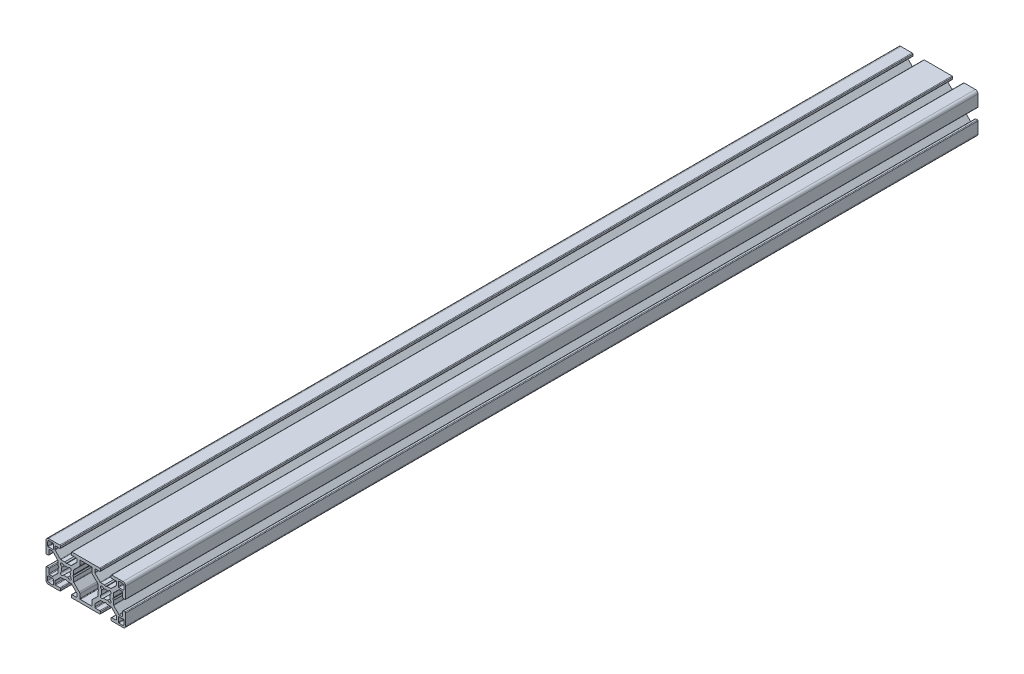
SolidWorks part; units mm, degrees
material "6105-T5 Aluminum"
ref_plane "Front Plane" through (0, 0, 0) normal (0, 0, 1) x (1, 0, 0)
ref_plane "Top Plane" through (0, 0, 0) normal (0, 1, 0) x (1, 0, 0)
ref_plane "Right Plane" through (0, 0, 0) normal (1, 0, 0) x (0, 0, -1)
sketch "Sketch1" plane through (0, 0, 0) normal (0, 0, 1) x (1, 0, 0)
  line L0 (12.7825, 3.7261) -> (13.5257, 2.983)
  line L1 (16.4743, 2.983) -> (17.2175, 3.7261)
  line L2 (18.7261, 2.2175) -> (17.983, 1.4743)
  line L3 (17.983, -1.4743) -> (18.7261, -2.2175)
  line L4 (17.2175, -3.7261) -> (16.4743, -2.983)
  line L5 (13.5257, -2.983) -> (12.7825, -3.7261)
  line L6 (11.2739, -2.2175) -> (12.017, -1.4743)
  line L7 (12.017, 1.4743) -> (11.2739, 2.2175)
  line L8 (-28.7046, 9.8946) -> (-28.7046, 12.6886)
  line L9 (-27.6886, 13.7046) -> (-24.8946, 13.7046)
  line L10 (-24.5136, 13.3236) -> (-24.5136, 9.8946)
  line L11 (-24.8946, 9.5136) -> (-28.3236, 9.5136)
  line L12 (-24.8946, -13.7046) -> (-27.6886, -13.7046)
  line L13 (-28.7046, -12.6886) -> (-28.7046, -9.8946)
  line L14 (-28.3236, -9.5136) -> (-24.8946, -9.5136)
  line L15 (-24.5136, -9.8946) -> (-24.5136, -13.3236)
  line L16 (4.9816, 8.2224) -> (9.0292, 4.1748)
  line L17 (9.178, 3.8155) -> (9.178, 0.9525)
  line L18 (9.178, 0.9525) -> (9.686, 0)
  line L19 (9.686, 0) -> (9.178, -0.9525)
  line L20 (9.178, -0.9525) -> (9.178, -3.8155)
  line L21 (9.0292, -4.1748) -> (4.9816, -8.2224)
  line L22 (4.5352, -9.3) -> (4.5352, -12.4092)
  line L23 (4.1542, -12.7902) -> (-4.1542, -12.7902)
  line L24 (-4.5352, -12.4092) -> (-4.5352, -9.3)
  line L25 (-4.9816, -8.2224) -> (-9.0292, -4.1748)
  line L26 (-9.178, -3.8155) -> (-9.178, -0.9525)
  line L27 (-9.178, -0.9525) -> (-9.686, 0)
  line L28 (-9.686, 0) -> (-9.178, 0.9525)
  line L29 (-9.178, 0.9525) -> (-9.178, 3.8155)
  line L30 (-9.0292, 4.1748) -> (-4.9816, 8.2224)
  line L31 (-4.5352, 9.3) -> (-4.5352, 12.4092)
  line L32 (-4.1542, 12.7902) -> (4.1542, 12.7902)
  line L33 (4.5352, 12.4092) -> (4.5352, 9.3)
  line L34 (-18.7261, -2.2175) -> (-17.983, -1.4743)
  line L35 (-17.983, 1.4743) -> (-18.7261, 2.2175)
  line L36 (-17.2175, 3.7261) -> (-16.4743, 2.983)
  line L37 (-13.5257, 2.983) -> (-12.7825, 3.7261)
  line L38 (-11.2739, 2.2175) -> (-12.017, 1.4743)
  line L39 (-12.017, -1.4743) -> (-11.2739, -2.2175)
  line L40 (-12.7825, -3.7261) -> (-13.5257, -2.983)
  line L41 (-16.4743, -2.983) -> (-17.2175, -3.7261)
  line L42 (24.8946, 13.7046) -> (27.6886, 13.7046)
  line L43 (28.7046, 12.6886) -> (28.7046, 9.8946)
  line L44 (28.3236, 9.5136) -> (24.8946, 9.5136)
  line L45 (24.5136, 9.8946) -> (24.5136, 13.3236)
  line L46 (24.5136, -13.3236) -> (24.5136, -9.8946)
  line L47 (24.8946, -9.5136) -> (28.3236, -9.5136)
  line L48 (28.7046, -9.8946) -> (28.7046, -12.6886)
  line L49 (27.6886, -13.7046) -> (24.8946, -13.7046)
  line L50 (-10.428, -15) -> (10.428, -15)
  line L51 (10.936, -14.492) -> (10.936, -13.2982)
  line L52 (10.428, -12.7902) -> (7.253, -12.7902)
  line L53 (6.745, -12.2822) -> (6.745, -10.2615)
  line L54 (6.8938, -9.9023) -> (10.8252, -5.9708)
  line L55 (11.1845, -5.822) -> (14.0475, -5.822)
  line L56 (14.0475, -5.822) -> (15, -5.314)
  line L57 (15, -5.314) -> (15.9525, -5.822)
  line L58 (15.9525, -5.822) -> (18.8155, -5.822)
  line L59 (19.1748, -5.9708) -> (23.1062, -9.9023)
  line L60 (23.255, -10.2615) -> (23.255, -12.2822)
  line L61 (22.747, -12.7902) -> (19.572, -12.7902)
  line L62 (19.064, -13.2982) -> (19.064, -14.492)
  line L63 (19.572, -15) -> (27.9934, -15)
  line L64 (30, -12.9934) -> (30, -4.572)
  line L65 (29.492, -4.064) -> (28.2982, -4.064)
  line L66 (27.7902, -4.572) -> (27.7902, -7.747)
  line L67 (27.2822, -8.255) -> (25.2615, -8.255)
  line L68 (24.9023, -8.1062) -> (20.9708, -4.1748)
  line L69 (20.822, -3.8155) -> (20.822, -0.9525)
  line L70 (20.822, -0.9525) -> (20.314, 0)
  line L71 (20.314, 0) -> (20.822, 0.9525)
  line L72 (20.822, 0.9525) -> (20.822, 3.8155)
  line L73 (20.9708, 4.1748) -> (24.9023, 8.1062)
  line L74 (25.2615, 8.255) -> (27.2822, 8.255)
  line L75 (27.7902, 7.747) -> (27.7902, 4.572)
  line L76 (28.2982, 4.064) -> (29.492, 4.064)
  line L77 (30, 4.572) -> (30, 12.9934)
  line L78 (27.9934, 15) -> (19.572, 15)
  line L79 (19.064, 14.492) -> (19.064, 13.2982)
  line L80 (19.572, 12.7902) -> (22.747, 12.7902)
  line L81 (23.255, 12.2822) -> (23.255, 10.2615)
  line L82 (23.1062, 9.9023) -> (19.1748, 5.9708)
  line L83 (18.8155, 5.822) -> (15.9525, 5.822)
  line L84 (15.9525, 5.822) -> (15, 5.314)
  line L85 (15, 5.314) -> (14.0475, 5.822)
  line L86 (14.0475, 5.822) -> (11.1845, 5.822)
  line L87 (10.8252, 5.9708) -> (6.8938, 9.9023)
  line L88 (6.745, 10.2615) -> (6.745, 12.2822)
  line L89 (7.253, 12.7902) -> (10.428, 12.7902)
  line L90 (10.936, 13.2982) -> (10.936, 14.492)
  line L91 (10.428, 15) -> (-10.428, 15)
  line L92 (-10.936, 14.492) -> (-10.936, 13.2982)
  line L93 (-10.428, 12.7902) -> (-7.253, 12.7902)
  line L94 (-6.745, 12.2822) -> (-6.745, 10.2615)
  line L95 (-6.8938, 9.9023) -> (-10.8252, 5.9708)
  line L96 (-11.1845, 5.822) -> (-14.0475, 5.822)
  line L97 (-14.0475, 5.822) -> (-15, 5.314)
  line L98 (-15, 5.314) -> (-15.9525, 5.822)
  line L99 (-15.9525, 5.822) -> (-18.8155, 5.822)
  line L100 (-19.1748, 5.9708) -> (-23.1062, 9.9023)
  line L101 (-23.255, 10.2615) -> (-23.255, 12.2822)
  line L102 (-22.747, 12.7902) -> (-19.572, 12.7902)
  line L103 (-19.064, 13.2982) -> (-19.064, 14.492)
  line L104 (-19.572, 15) -> (-27.9934, 15)
  line L105 (-30, 12.9934) -> (-30, 4.572)
  line L106 (-29.492, 4.064) -> (-28.2982, 4.064)
  line L107 (-27.7902, 4.572) -> (-27.7902, 7.747)
  line L108 (-27.2822, 8.255) -> (-25.2615, 8.255)
  line L109 (-24.9023, 8.1062) -> (-20.9708, 4.1748)
  line L110 (-20.822, 3.8155) -> (-20.822, 0.9525)
  line L111 (-20.822, 0.9525) -> (-20.314, 0)
  line L112 (-20.314, 0) -> (-20.822, -0.9525)
  line L113 (-20.822, -0.9525) -> (-20.822, -3.8155)
  line L114 (-20.9708, -4.1748) -> (-24.9023, -8.1062)
  line L115 (-25.2615, -8.255) -> (-27.2822, -8.255)
  line L116 (-27.7902, -7.747) -> (-27.7902, -4.572)
  line L117 (-28.2982, -4.064) -> (-29.492, -4.064)
  line L118 (-30, -4.572) -> (-30, -12.9934)
  line L119 (-27.9934, -15) -> (-19.572, -15)
  line L120 (-19.064, -14.492) -> (-19.064, -13.2982)
  line L121 (-19.572, -12.7902) -> (-22.747, -12.7902)
  line L122 (-23.255, -12.2822) -> (-23.255, -10.2615)
  line L123 (-23.1062, -9.9023) -> (-19.1748, -5.9708)
  line L124 (-18.8155, -5.822) -> (-15.9525, -5.822)
  line L125 (-15.9525, -5.822) -> (-15, -5.314)
  line L126 (-15, -5.314) -> (-14.0475, -5.822)
  line L127 (-14.0475, -5.822) -> (-11.1845, -5.822)
  line L128 (-10.8252, -5.9708) -> (-6.8938, -9.9023)
  line L129 (-6.745, -10.2615) -> (-6.745, -12.2822)
  line L130 (-7.253, -12.7902) -> (-10.428, -12.7902)
  line L131 (-10.936, -13.2982) -> (-10.936, -14.492)
  arc A0 (12.7825, 3.7261) -> (11.2739, 2.2175) centre (12.0282, 2.9718) ccw
  arc A1 (16.4743, 2.983) -> (13.5257, 2.983) centre (15, 0) ccw
  arc A2 (18.7261, 2.2175) -> (17.2175, 3.7261) centre (17.9718, 2.9718) ccw
  arc A3 (17.983, -1.4743) -> (17.983, 1.4743) centre (15, 0) ccw
  arc A4 (17.2175, -3.7261) -> (18.7261, -2.2175) centre (17.9718, -2.9718) ccw
  arc A5 (13.5257, -2.983) -> (16.4743, -2.983) centre (15, 0) ccw
  arc A6 (11.2739, -2.2175) -> (12.7825, -3.7261) centre (12.0282, -2.9718) ccw
  arc A7 (12.017, 1.4743) -> (12.017, -1.4743) centre (15, 0) ccw
  arc A8 (-28.7046, 9.8946) -> (-28.3236, 9.5136) centre (-28.3236, 9.8946) ccw
  arc A9 (-27.6886, 13.7046) -> (-28.7046, 12.6886) centre (-27.6886, 12.6886) ccw
  arc A10 (-24.5136, 13.3236) -> (-24.8946, 13.7046) centre (-24.8946, 13.3236) ccw
  arc A11 (-24.8946, 9.5136) -> (-24.5136, 9.8946) centre (-24.8946, 9.8946) ccw
  arc A12 (-24.8946, -13.7046) -> (-24.5136, -13.3236) centre (-24.8946, -13.3236) ccw
  arc A13 (-28.7046, -12.6886) -> (-27.6886, -13.7046) centre (-27.6886, -12.6886) ccw
  arc A14 (-28.3236, -9.5136) -> (-28.7046, -9.8946) centre (-28.3236, -9.8946) ccw
  arc A15 (-24.5136, -9.8946) -> (-24.8946, -9.5136) centre (-24.8946, -9.8946) ccw
  arc A16 (4.5352, 9.3) -> (4.9816, 8.2224) centre (6.0592, 9.3) ccw
  arc A17 (9.178, 3.8155) -> (9.0292, 4.1748) centre (8.67, 3.8155) ccw
  arc A18 (9.0292, -4.1748) -> (9.178, -3.8155) centre (8.67, -3.8155) ccw
  arc A19 (4.9816, -8.2224) -> (4.5352, -9.3) centre (6.0592, -9.3) ccw
  arc A20 (4.1542, -12.7902) -> (4.5352, -12.4092) centre (4.1542, -12.4092) ccw
  arc A21 (-4.5352, -12.4092) -> (-4.1542, -12.7902) centre (-4.1542, -12.4092) ccw
  arc A22 (-4.5352, -9.3) -> (-4.9816, -8.2224) centre (-6.0592, -9.3) ccw
  arc A23 (-9.178, -3.8155) -> (-9.0292, -4.1748) centre (-8.67, -3.8155) ccw
  arc A24 (-9.0292, 4.1748) -> (-9.178, 3.8155) centre (-8.67, 3.8155) ccw
  arc A25 (-4.9816, 8.2224) -> (-4.5352, 9.3) centre (-6.0592, 9.3) ccw
  arc A26 (-4.1542, 12.7902) -> (-4.5352, 12.4092) centre (-4.1542, 12.4092) ccw
  arc A27 (4.5352, 12.4092) -> (4.1542, 12.7902) centre (4.1542, 12.4092) ccw
  arc A28 (-18.7261, -2.2175) -> (-17.2175, -3.7261) centre (-17.9718, -2.9718) ccw
  arc A29 (-17.983, 1.4743) -> (-17.983, -1.4743) centre (-15, 0) ccw
  arc A30 (-17.2175, 3.7261) -> (-18.7261, 2.2175) centre (-17.9718, 2.9718) ccw
  arc A31 (-13.5257, 2.983) -> (-16.4743, 2.983) centre (-15, 0) ccw
  arc A32 (-11.2739, 2.2175) -> (-12.7825, 3.7261) centre (-12.0282, 2.9718) ccw
  arc A33 (-12.017, -1.4743) -> (-12.017, 1.4743) centre (-15, 0) ccw
  arc A34 (-12.7825, -3.7261) -> (-11.2739, -2.2175) centre (-12.0282, -2.9718) ccw
  arc A35 (-16.4743, -2.983) -> (-13.5257, -2.983) centre (-15, 0) ccw
  arc A36 (24.8946, 13.7046) -> (24.5136, 13.3236) centre (24.8946, 13.3236) ccw
  arc A37 (28.7046, 12.6886) -> (27.6886, 13.7046) centre (27.6886, 12.6886) ccw
  arc A38 (28.3236, 9.5136) -> (28.7046, 9.8946) centre (28.3236, 9.8946) ccw
  arc A39 (24.5136, 9.8946) -> (24.8946, 9.5136) centre (24.8946, 9.8946) ccw
  arc A40 (24.5136, -13.3236) -> (24.8946, -13.7046) centre (24.8946, -13.3236) ccw
  arc A41 (24.8946, -9.5136) -> (24.5136, -9.8946) centre (24.8946, -9.8946) ccw
  arc A42 (28.7046, -9.8946) -> (28.3236, -9.5136) centre (28.3236, -9.8946) ccw
  arc A43 (27.6886, -13.7046) -> (28.7046, -12.6886) centre (27.6886, -12.6886) ccw
  arc A44 (10.428, -15) -> (10.936, -14.492) centre (10.428, -14.492) ccw
  arc A45 (10.936, -13.2982) -> (10.428, -12.7902) centre (10.428, -13.2982) ccw
  arc A46 (6.745, -12.2822) -> (7.253, -12.7902) centre (7.253, -12.2822) ccw
  arc A47 (6.8938, -9.9023) -> (6.745, -10.2615) centre (7.253, -10.2615) ccw
  arc A48 (11.1845, -5.822) -> (10.8252, -5.9708) centre (11.1845, -6.33) ccw
  arc A49 (19.1748, -5.9708) -> (18.8155, -5.822) centre (18.8155, -6.33) ccw
  arc A50 (23.255, -10.2615) -> (23.1062, -9.9023) centre (22.747, -10.2615) ccw
  arc A51 (22.747, -12.7902) -> (23.255, -12.2822) centre (22.747, -12.2822) ccw
  arc A52 (19.572, -12.7902) -> (19.064, -13.2982) centre (19.572, -13.2982) ccw
  arc A53 (19.064, -14.492) -> (19.572, -15) centre (19.572, -14.492) ccw
  arc A54 (27.9934, -15) -> (30, -12.9934) centre (27.9934, -12.9934) ccw
  arc A55 (30, -4.572) -> (29.492, -4.064) centre (29.492, -4.572) ccw
  arc A56 (28.2982, -4.064) -> (27.7902, -4.572) centre (28.2982, -4.572) ccw
  arc A57 (27.2822, -8.255) -> (27.7902, -7.747) centre (27.2822, -7.747) ccw
  arc A58 (24.9023, -8.1062) -> (25.2615, -8.255) centre (25.2615, -7.747) ccw
  arc A59 (20.822, -3.8155) -> (20.9708, -4.1748) centre (21.33, -3.8155) ccw
  arc A60 (20.9708, 4.1748) -> (20.822, 3.8155) centre (21.33, 3.8155) ccw
  arc A61 (25.2615, 8.255) -> (24.9023, 8.1062) centre (25.2615, 7.747) ccw
  arc A62 (27.7902, 7.747) -> (27.2822, 8.255) centre (27.2822, 7.747) ccw
  arc A63 (27.7902, 4.572) -> (28.2982, 4.064) centre (28.2982, 4.572) ccw
  arc A64 (29.492, 4.064) -> (30, 4.572) centre (29.492, 4.572) ccw
  arc A65 (30, 12.9934) -> (27.9934, 15) centre (27.9934, 12.9934) ccw
  arc A66 (19.572, 15) -> (19.064, 14.492) centre (19.572, 14.492) ccw
  arc A67 (19.064, 13.2982) -> (19.572, 12.7902) centre (19.572, 13.2982) ccw
  arc A68 (23.255, 12.2822) -> (22.747, 12.7902) centre (22.747, 12.2822) ccw
  arc A69 (23.1062, 9.9023) -> (23.255, 10.2615) centre (22.747, 10.2615) ccw
  arc A70 (18.8155, 5.822) -> (19.1748, 5.9708) centre (18.8155, 6.33) ccw
  arc A71 (10.8252, 5.9708) -> (11.1845, 5.822) centre (11.1845, 6.33) ccw
  arc A72 (6.745, 10.2615) -> (6.8938, 9.9023) centre (7.253, 10.2615) ccw
  arc A73 (7.253, 12.7902) -> (6.745, 12.2822) centre (7.253, 12.2822) ccw
  arc A74 (10.428, 12.7902) -> (10.936, 13.2982) centre (10.428, 13.2982) ccw
  arc A75 (10.936, 14.492) -> (10.428, 15) centre (10.428, 14.492) ccw
  arc A76 (-10.428, 15) -> (-10.936, 14.492) centre (-10.428, 14.492) ccw
  arc A77 (-10.936, 13.2982) -> (-10.428, 12.7902) centre (-10.428, 13.2982) ccw
  arc A78 (-6.745, 12.2822) -> (-7.253, 12.7902) centre (-7.253, 12.2822) ccw
  arc A79 (-6.8938, 9.9023) -> (-6.745, 10.2615) centre (-7.253, 10.2615) ccw
  arc A80 (-11.1845, 5.822) -> (-10.8252, 5.9708) centre (-11.1845, 6.33) ccw
  arc A81 (-19.1748, 5.9708) -> (-18.8155, 5.822) centre (-18.8155, 6.33) ccw
  arc A82 (-23.255, 10.2615) -> (-23.1062, 9.9023) centre (-22.747, 10.2615) ccw
  arc A83 (-22.747, 12.7902) -> (-23.255, 12.2822) centre (-22.747, 12.2822) ccw
  arc A84 (-19.572, 12.7902) -> (-19.064, 13.2982) centre (-19.572, 13.2982) ccw
  arc A85 (-19.064, 14.492) -> (-19.572, 15) centre (-19.572, 14.492) ccw
  arc A86 (-27.9934, 15) -> (-30, 12.9934) centre (-27.9934, 12.9934) ccw
  arc A87 (-30, 4.572) -> (-29.492, 4.064) centre (-29.492, 4.572) ccw
  arc A88 (-28.2982, 4.064) -> (-27.7902, 4.572) centre (-28.2982, 4.572) ccw
  arc A89 (-27.2822, 8.255) -> (-27.7902, 7.747) centre (-27.2822, 7.747) ccw
  arc A90 (-24.9023, 8.1062) -> (-25.2615, 8.255) centre (-25.2615, 7.747) ccw
  arc A91 (-20.822, 3.8155) -> (-20.9708, 4.1748) centre (-21.33, 3.8155) ccw
  arc A92 (-20.9708, -4.1748) -> (-20.822, -3.8155) centre (-21.33, -3.8155) ccw
  arc A93 (-25.2615, -8.255) -> (-24.9023, -8.1062) centre (-25.2615, -7.747) ccw
  arc A94 (-27.7902, -7.747) -> (-27.2822, -8.255) centre (-27.2822, -7.747) ccw
  arc A95 (-27.7902, -4.572) -> (-28.2982, -4.064) centre (-28.2982, -4.572) ccw
  arc A96 (-29.492, -4.064) -> (-30, -4.572) centre (-29.492, -4.572) ccw
  arc A97 (-30, -12.9934) -> (-27.9934, -15) centre (-27.9934, -12.9934) ccw
  arc A98 (-19.572, -15) -> (-19.064, -14.492) centre (-19.572, -14.492) ccw
  arc A99 (-19.064, -13.2982) -> (-19.572, -12.7902) centre (-19.572, -13.2982) ccw
  arc A100 (-23.255, -12.2822) -> (-22.747, -12.7902) centre (-22.747, -12.2822) ccw
  arc A101 (-23.1062, -9.9023) -> (-23.255, -10.2615) centre (-22.747, -10.2615) ccw
  arc A102 (-18.8155, -5.822) -> (-19.1748, -5.9708) centre (-18.8155, -6.33) ccw
  arc A103 (-10.8252, -5.9708) -> (-11.1845, -5.822) centre (-11.1845, -6.33) ccw
  arc A104 (-6.745, -10.2615) -> (-6.8938, -9.9023) centre (-7.253, -10.2615) ccw
  arc A105 (-7.253, -12.7902) -> (-6.745, -12.2822) centre (-7.253, -12.2822) ccw
  arc A106 (-10.428, -12.7902) -> (-10.936, -13.2982) centre (-10.428, -13.2982) ccw
  arc A107 (-10.936, -14.492) -> (-10.428, -15) centre (-10.428, -14.492) ccw
extrude "Extrude1" add sketch "Sketch1" against normal blind 642
